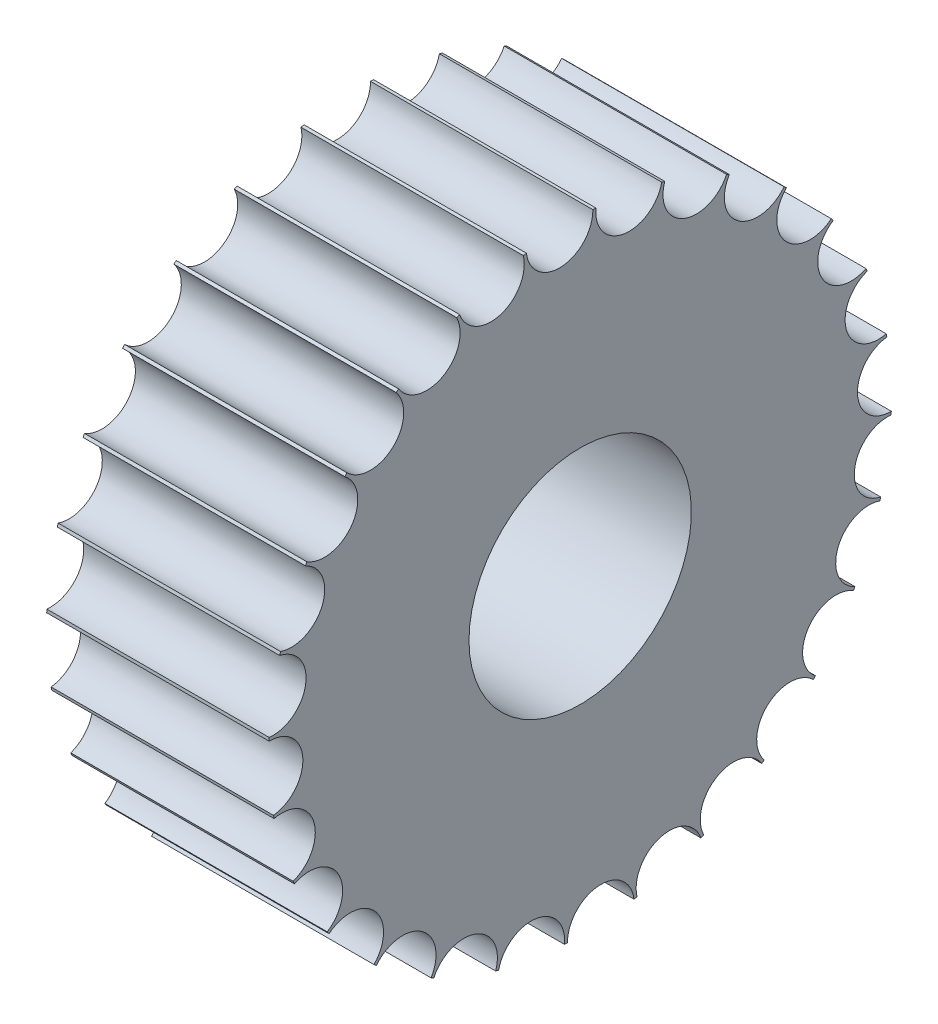
SolidWorks part; units mm, degrees
ref_plane "前视基准面" through (0, 0, 0) normal (0, 0, 1) x (1, 0, 0)
ref_plane "上视基准面" through (0, 0, 0) normal (0, 1, 0) x (1, 0, 0)
ref_plane "右视基准面" through (0, 0, 0) normal (1, 0, 0) x (0, 0, -1)
sketch "草图1" plane through (0, 0, 0) normal (0, 0, 1) x (1, 0, 0)
  line L0 (-4.5375, 10.7833) -> (-14.5375, 10.7833)
  line L1 (-37.9515, -3.2167) -> (41.3993, -3.2167) construction
  line L2 (-14.5375, 10.7833) -> (-14.5375, 1.7833)
  line L3 (-15.7875, 1.7833) -> (-14.5375, 1.7833)
  line L4 (-15.7875, 1.7833) -> (-15.7875, -3.2167)
  line L6 (-3.2875, 1.7833) -> (-3.2875, -3.2167)
  line L7 (-3.2875, 1.7833) -> (-4.5375, 1.7833)
  line L8 (-4.5375, 10.7833) -> (-4.5375, 1.7833)
  line L9 (-15.7875, -3.2167) -> (-3.2875, -3.2167)
  dimension "D1" = 10
  dimension "D2" = 14
  dimension "D3" = 5
  dimension "D4" = 1.25
revolve "旋转1" add sketch "草图1" angle 360 about L1
sketch "草图2" plane through (-14.5375, 0, 0) normal (-1, 0, 0) x (0, 0, 1)
  arc A0 (-0.5698, 10.7717) -> (2.4193, 10.5727) centre (0.9301, 10.7524) ccw
  circle A1 centre (0, -3.2167) radius 14
  circle A2 centre (0, -3.2167) radius 14
  circle M3 centre (0, -3.2167) radius 14
  dimension "D2" = 3
  dimension "D1" = 0
extrude "切除-拉伸1" cut sketch "草图2" against normal blind 10 contours A0 M3
pattern_circular "阵列(圆周)2" count 28 over 360 about axis through (0, -3.2167, 0) along (1, 0, 0) of "切除-拉伸1"
sketch "草图3" plane through (-15.7875, 0, 0) normal (-1, 0, 0) x (0, 0, 1)
  circle A0 centre (0, -3.2167) radius 5
  dimension "D1" = 10
extrude "切除-拉伸2" cut sketch "草图3" against normal through all
